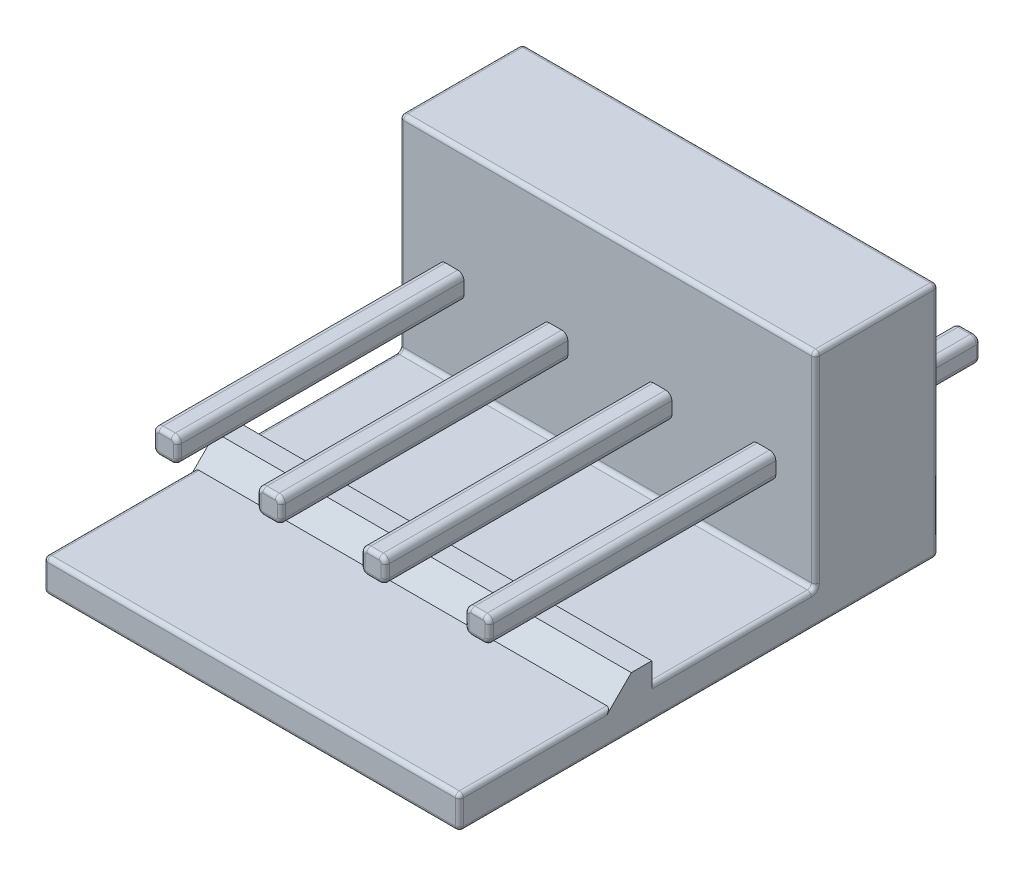
SolidWorks part; units mm, degrees
ref_plane "前视基准面" through (0, 0, 0) normal (0, 0, 1) x (1, 0, 0)
ref_plane "上视基准面" through (0, 0, 0) normal (0, 1, 0) x (1, 0, 0)
ref_plane "右视基准面" through (0, 0, 0) normal (1, 0, 0) x (0, 0, -1)
sketch "草图1" plane through (0, 0, 0) normal (0, 0, 1) x (1, 0, 0)
  line L0 (-1000, 0) -> (49000, 0) construction
  line L1 (0, -1000) -> (0, 49000) construction
  line L2 (-5.08, 2.9) -> (-5.08, -2.9)
  line L3 (-5.08, -2.9) -> (5.08, -2.9)
  line L4 (-5.08, 2.9) -> (5.08, 2.9)
  line L5 (5.08, 2.9) -> (5.08, -2.9)
  point P10 (-5.08, 0)
  point P11 (0, -2.9)
  point P12 (0, 2.9)
  dimension "D1" = 10.16
  dimension "D2" = 5.8
extrude "凸台-拉伸1" add sketch "草图1" along normal blind 11.7
sketch "草图2" plane through (5.08, 0, 0) normal (1, 0, 0) x (0, 0, -1)
  line L0 (-11.7, -2.1) -> (-8, -2.1)
  line L1 (-11.7, -2.9) -> (-11.7, 2.9) construction
  line L2 (-3, -2.1) -> (-3, 2.9)
  line L3 (-11.7, 2.9) -> (0, 2.9) construction
  line L4 (-3, 2.9) -> (-11.7, 2.9)
  line L5 (-11.7, 2.9) -> (-11.7, -2.1)
  line L6 (0, -2.9) -> (0, 2.9) construction
  line L7 (-11.7, -2.9) -> (0, -2.9) construction
  line L8 (-7.5, -1.6) -> (-7, -1.6)
  line L9 (-7, -2.1) -> (-7, -1.6)
  line L10 (-7, -2.1) -> (-3, -2.1)
  line L12 (-8, -2.1) -> (-7.5, -1.6)
  dimension "D1" = 3
  dimension "D2" = 0.8
  dimension "D3" = 0.5
  dimension "D4" = 4
extrude "切除-拉伸1" cut sketch "草图2" against normal through all
sketch "草图3" plane through (0, 0, 0) normal (0, 0, -1) x (-1, 0, 0)
  line L0 (-5.08, 0) -> (5.08, 0) construction
  line L1 (-5.08, -2.9) -> (-5.08, 2.9) construction
  line L2 (5.08, 2.9) -> (5.08, -2.9) construction
  line L3 (0, -2.9) -> (0, 2.9) construction
  line L4 (5.08, -2.9) -> (-5.08, -2.9) construction
  line L5 (-5.08, 2.9) -> (5.08, 2.9) construction
  line L6 (-1.27, -1.0013) -> (-1.27, 0.9265) construction
  line L7 (-1.57, -0.15) -> (-1.57, 0.15)
  line L8 (-1.42, -0.3) -> (-1.12, -0.3)
  line L9 (-0.97, -0.15) -> (-0.97, 0.15)
  line L10 (-1.42, 0.3) -> (-1.12, 0.3)
  line L11 (-4.11, -0.15) -> (-4.11, 0.15)
  line L12 (-3.96, 0.3) -> (-3.66, 0.3)
  line L13 (-3.51, -0.15) -> (-3.51, 0.15)
  line L14 (-3.96, -0.3) -> (-3.66, -0.3)
  arc A0 (-1.12, 0.3) -> (-0.97, 0.15) centre (-1.12, 0.15) cw
  arc A1 (-0.97, -0.15) -> (-1.12, -0.3) centre (-1.12, -0.15) cw
  arc A2 (-1.42, 0.3) -> (-1.57, 0.15) centre (-1.42, 0.15) ccw
  arc A3 (-1.57, -0.15) -> (-1.42, -0.3) centre (-1.42, -0.15) ccw
  arc A4 (-4.11, -0.15) -> (-3.96, -0.3) centre (-3.96, -0.15) ccw
  arc A5 (-3.96, 0.3) -> (-4.11, 0.15) centre (-3.96, 0.15) ccw
  arc A6 (-3.66, 0.3) -> (-3.51, 0.15) centre (-3.66, 0.15) cw
  arc A7 (-3.51, -0.15) -> (-3.66, -0.3) centre (-3.66, -0.15) cw
  point P18 (-1.27, -0.3)
  point P20 (-0.97, 0)
  point P21 (-1.57, 0)
  point P23 (-0.97, 0.3)
  point P26 (-0.97, -0.3)
  point P29 (-1.57, 0.3)
  point P32 (-1.57, -0.3)
  dimension "D4" = 0.15
  dimension "D1" = 1.27
  dimension "D2" = 0.6
  dimension "D3" = 0.6
  dimension "D5" = 2
extrude "凸台-拉伸2" add sketch "草图3" along normal blind 2 and the other way blind 10
fillet "圆角1" radius 0.1 32 edges at (1.5261, 0.2561, 10) (1.27, 0.3, 10) (1.0139, 0.2561, 10) (0.97, 0, 10) (1.0139, -0.2561, 10) (1.27, -0.3, 10) (1.5261, -0.2561, 10) (4.0661, 0.2561, 10) (3.81, 0.3, 10) (3.5539, 0.2561, 10) (3.51, 0, 10) (3.5539, -0.2561, 10) (3.81, -0.3, 10) (4.0661, -0.2561, 10) (1.0139, 0.2561, -2) (0.97, 0, -2) (1.0139, -0.2561, -2) (1.27, -0.3, -2) (1.5261, -0.2561, -2) (1.57, 0, -2) (1.5261, 0.2561, -2) (3.5539, 0.2561, -2) (3.51, 0, -2) (3.5539, -0.2561, -2) (3.81, -0.3, -2) (4.0661, -0.2561, -2) (4.11, 0, -2) (4.0661, 0.2561, -2) (1.57, 0, 10) (4.11, 0, 10) (1.27, 0.3, -2) (3.81, 0.3, -2)
mirror "镜向1" about plane through (0, 0, 0) normal (1, 0, 0) of "凸台-拉伸2", "圆角1"
fillet "圆角2" radius 0.1 20 edges at (-5.08, -2.1, 5) (5.08, -2.1, 5) (5.08, -2.1, 9.85) (5.08, -2.5, 11.7) (-5.08, -2.1, 9.85) (-5.08, -2.5, 11.7) (0, -2.1, 11.7) (5.08, -2.9, 5.85) (0, -2.9, 11.7) (-5.08, -2.9, 5.85) (0, -2.1, 3) (-5.08, 0.4, 3) (0, -2.9, 0) (-5.08, 0, 0) (5.08, 2.9, 1.5) (-5.08, 2.9, 1.5) (0, 2.9, 0) (5.08, 0, 0) (5.08, 0.4, 3) (0, 2.9, 3)
